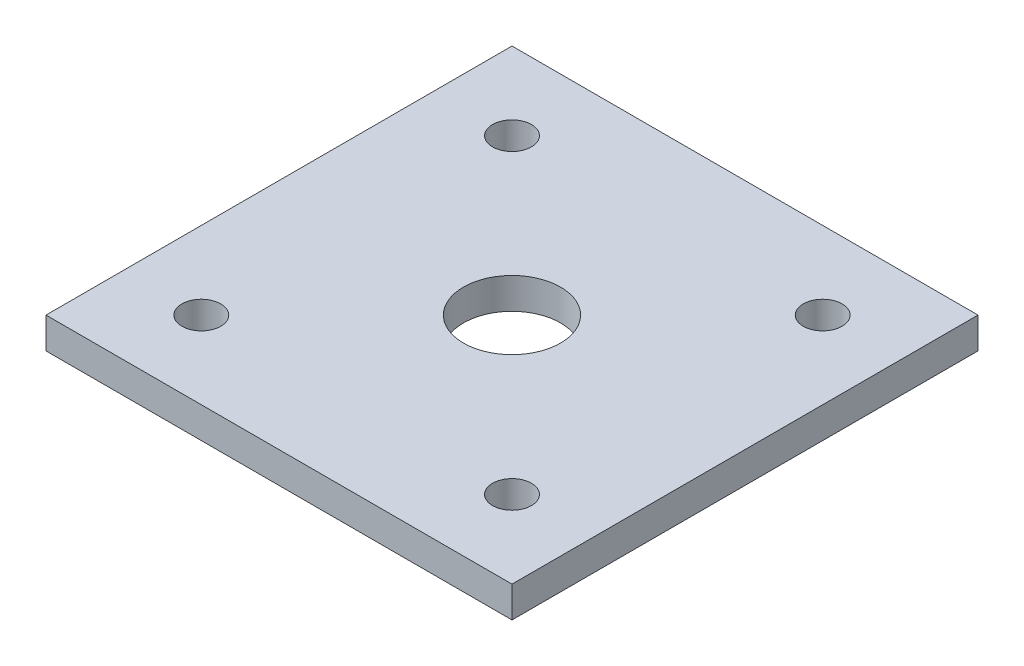
SolidWorks part; units mm, degrees
ref_plane "Front Plane" through (0, 0, 0) normal (0, 0, 1) x (1, 0, 0)
ref_plane "Top Plane" through (0, 0, 0) normal (0, 1, 0) x (1, 0, 0)
ref_plane "Right Plane" through (0, 0, 0) normal (1, 0, 0) x (0, 0, -1)
sketch "Sketch1" plane through (0, 0, 0) normal (0, 1, 0) x (1, 0, 0)
  line L1 (-60, 60) -> (60, 60)
  line L2 (-60, 60) -> (-60, -60)
  line L3 (-60, -60) -> (60, -60)
  line L4 (60, 60) -> (60, -60)
  line L5 (-60, 60) -> (60, -60) construction
  line L6 (-60, -60) -> (60, 60) construction
  point P0 (0, 0)
  dimension "D1" = 120
extrude "Boss-Extrude2" add sketch "Sketch1" along normal blind 8
sketch "Sketch4" plane through (0, 8, 0) normal (0, 1, 0) x (1, 0, 0)
  circle A0 centre (0, 0) radius 12.5
  dimension "D1" = 25
extrude "Cut-Extrude2" cut sketch "Sketch4" against normal through all
sketch "Sketch5" plane through (0, 8, 0) normal (0, 1, 0) x (1, 0, 0)
  line L0 (60, 60) -> (-60, 60) construction
  line L2 (-60, 60) -> (-60, -60) construction
  circle A0 centre (-40, 40) radius 5
  dimension "D3" = 10
  dimension "D1" = 20
  dimension "D2" = 20
extrude "Cut-Extrude3" cut sketch "Sketch5" against normal through all
mirror "Mirror1" about plane through (0, 0, 0) normal (1, 0, 0) of "Cut-Extrude3"
mirror "Mirror2" about plane through (0, 0, 0) normal (0, 0, 1) of "Mirror1", "Cut-Extrude3"
